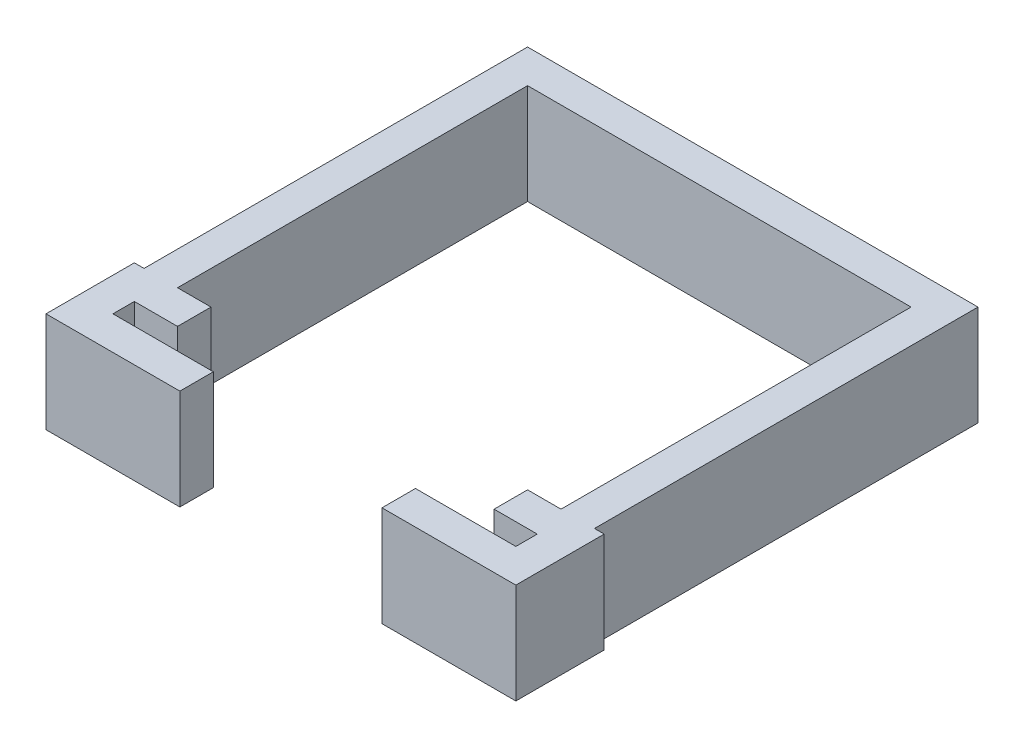
SolidWorks part; units mm, degrees
ref_plane "Спереди" through (0, 0, 0) normal (0, 0, 1) x (1, 0, 0)
ref_plane "Сверху" through (0, 0, 0) normal (0, 1, 0) x (1, 0, 0)
ref_plane "Справа" through (0, 0, 0) normal (1, 0, 0) x (0, 0, -1)
sketch "Эскиз1" plane through (0, 0, 0) normal (0, 1, 0) x (1, 0, 0)
  line L0 (-5, 5) -> (-5, 62.3)
  line L1 (-5, 62.3) -> (62.3, 62.3)
  line L2 (62.3, 62.3) -> (62.3, 5)
  line L3 (62.3, 5) -> (63.75, 5)
  line L4 (63.75, 5) -> (63.75, -8.2)
  line L5 (63.75, -8.2) -> (43.75, -8.2)
  line L6 (43.75, -8.2) -> (43.75, -3.2)
  line L7 (43.75, -3.2) -> (58.75, -3.2)
  line L8 (58.75, -3.2) -> (58.75, 0)
  line L9 (58.75, 0) -> (57.3, 0)
  line L10 (57.3, 0) -> (57.3, 57.3)
  line L11 (57.3, 57.3) -> (0, 57.3)
  line L12 (0, 57.3) -> (0, 0)
  line L13 (0, 0) -> (-1.45, 0)
  line L14 (-1.45, 0) -> (-1.45, -3.2)
  line L15 (-1.45, -3.2) -> (13.55, -3.2)
  line L16 (13.55, -3.2) -> (13.55, -8.2)
  line L17 (13.55, -8.2) -> (-6.45, -8.2)
  line L18 (-6.45, -8.2) -> (-6.45, 5)
  line L19 (-6.45, 5) -> (-5, 5)
  dimension "D1" = 57.3
  dimension "x" = 57.3
  dimension "D2" = 5
  dimension "d" = 5
  dimension "D3" = 5
  dimension "D4" = 5
  dimension "D5" = 5
  dimension "D6" = 3.2
  dimension "D7" = 60.2
  dimension "D8" = 20
extrude "Вытянуть1" add sketch "Эскиз1" along normal blind 15
sketch "Эскиз3" plane through (0, 0, 0) normal (0, 1, 0) x (1, 0, 0)
  line L1 (0, 0) -> (5, 0)
  line L2 (0, 0) -> (0, 5)
  line L3 (0, 5) -> (5, 5)
  line L4 (5, 0) -> (5, 5)
  line L5 (57.3, 0) -> (52.3, 0)
  line L6 (57.3, 0) -> (57.3, 5)
  line L7 (57.3, 5) -> (52.3, 5)
  line L8 (52.3, 0) -> (52.3, 5)
  dimension "D1" = 5
  dimension "D2" = 5
extrude "Вытянуть3" add sketch "Эскиз3" along normal blind 15
sketch "Эскиз4" plane through (0, 0, 3.2) normal (0, 0, -1) x (-1, 0, 0)
  line L0 (-13.55, 0) -> (1.45, 0) construction
  line L1 (-58.75, 0) -> (-43.75, 0) construction
  line L2 (1.45, 15) -> (1.45, 0) construction
  line L3 (-58.75, 15) -> (-58.75, 0) construction
  circle A0 centre (-8.65, 2.15) radius 2.15
  circle A1 centre (-48.65, 2.15) radius 2.15
  dimension "D1" = 4.3
  dimension "D2" = 10.1
  dimension "D3" = 10.1
extrude "Вытянуть4" add sketch "Эскиз4" along normal blind 2
equation "\"D2@Эскиз1\" = \"d\""
equation "\"D3@Эскиз1\" = \"d\""
equation "\"D4@Эскиз1\" = \"d\""
equation "\"D5@Эскиз1\" = \"d\""
equation "\"D1@Эскиз1\" = \"x\""
equation "\"D1@Эскиз3\" = \"d\""
equation "\"D2@Эскиз3\" = \"d\""
